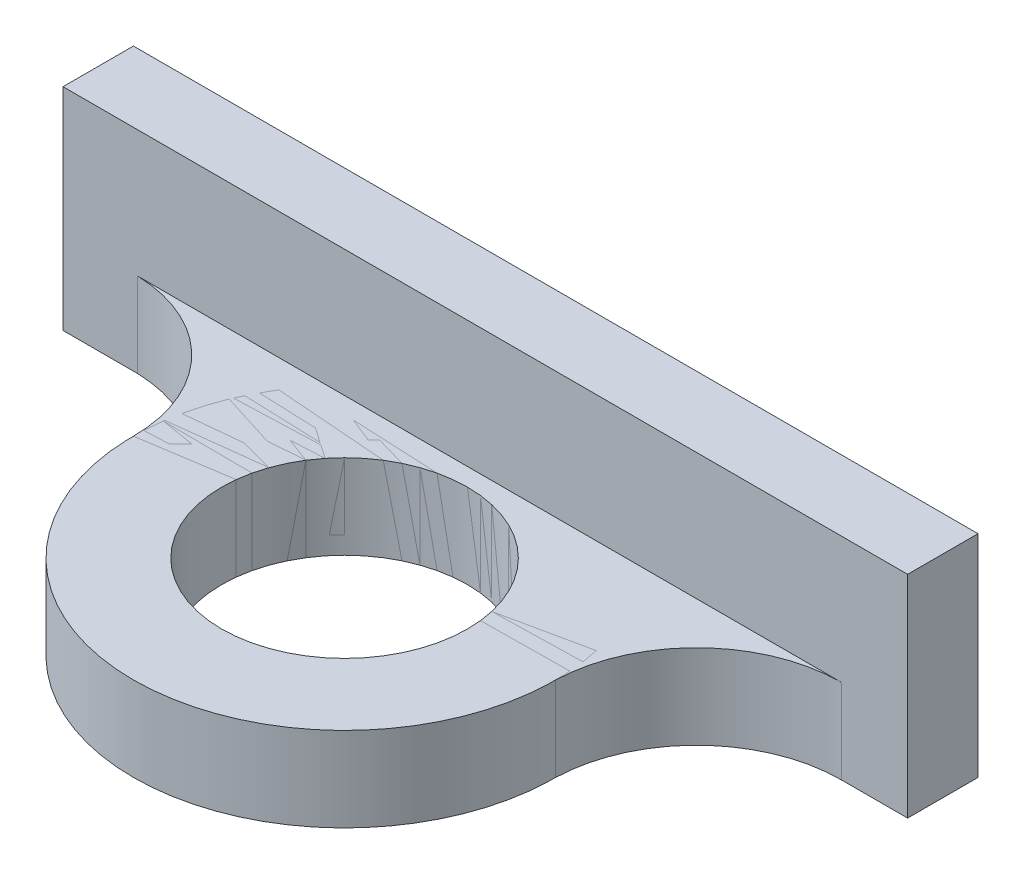
SolidWorks part; units mm, degrees
ref_plane "Front Plane" through (0, 0, 0) normal (0, 0, 1) x (1, 0, 0)
ref_plane "Top Plane" through (0, 0, 0) normal (0, 1, 0) x (1, 0, 0)
ref_plane "Right Plane" through (0, 0, 0) normal (1, 0, 0) x (0, 0, -1)
sketch "Sketch1" plane through (0, 0, 0) normal (0, 1, 0) x (1, 0, 0)
  circle A0 centre (0, 0) radius 17.4625
  circle A1 centre (0, 0) radius 30
  point P0 (0, 0)
  dimension "D2" = 34.925
  dimension "D1" = 60
extrude "Boss-Extrude1" add sketch "Sketch1" along normal blind 12
sketch "Sketch5" plane through (0, 0, 0) normal (0, -1, 0) x (1, 0, 0)
  line L1 (0, -30) -> (60, -30)
  line L4 (60, -30) -> (60, -20)
  line L5 (0, -30) -> (-60, -30)
  line L6 (60, -20) -> (0, -20)
  line L7 (0, -20) -> (-60, -20)
  line L8 (-60, -30) -> (-60, -20)
  point P3 (0, -30)
  point P15 (0, 0)
  dimension "D2" = 60
  dimension "D3" = 10
  dimension "D4" = 60
extrude "Boss-Extrude2" add sketch "Sketch5" against normal blind 30
sketch "Sketch6" plane through (0, 0, 0) normal (0, -1, 0) x (1, 0, 0)
  line L0 (-50.5902, -20) -> (50.5902, -20)
  line L2 (-30, 0) -> (-17.4625, 0)
  line L5 (30, 0) -> (17.4625, 0)
  arc A0 (22.3607, -20) -> (-22.3607, -20) centre (0, 0) ccw construction
  arc A1 (-30, 0) -> (-50.5902, -20) centre (-50.0085, 0) cw
  circle A2 centre (0, 0) radius 17.4625 construction
  arc A3 (50.5902, -20) -> (30, 0) centre (50.5902, 0.5989) cw
  arc A4 (-17.4625, 0) -> (17.4625, 0) centre (0, 0) ccw
  point P19 (0, 0)
  arc M1 (22.3607, -20) -> (-22.3607, -20) centre (0, 0) ccw
  line M2 (-22.3607, -20) -> (-60, -20)
  line M6 (60, -20) -> (22.3607, -20)
  circle M7 centre (0, 0) radius 17.4625
extrude "Boss-Extrude3" add sketch "Sketch6" against normal blind 12 separate body contours L5 L2 L0 M1 M7 | A3 M6 M1 | A1 M1 M2
ref_point "Point1"
sketch "Alignment Sketch" plane through (0, 0, -30) normal (0, 0, -1) x (-1, 0, 0)
  line L0 (60, 15) -> (-60, 15) construction
  line L1 (60, 30) -> (60, 0) construction
  line L2 (-60, 30) -> (-60, 0) construction
  line L3 (0, 0) -> (0, 30) construction
  line L4 (60, 30) -> (-60, 30) construction
